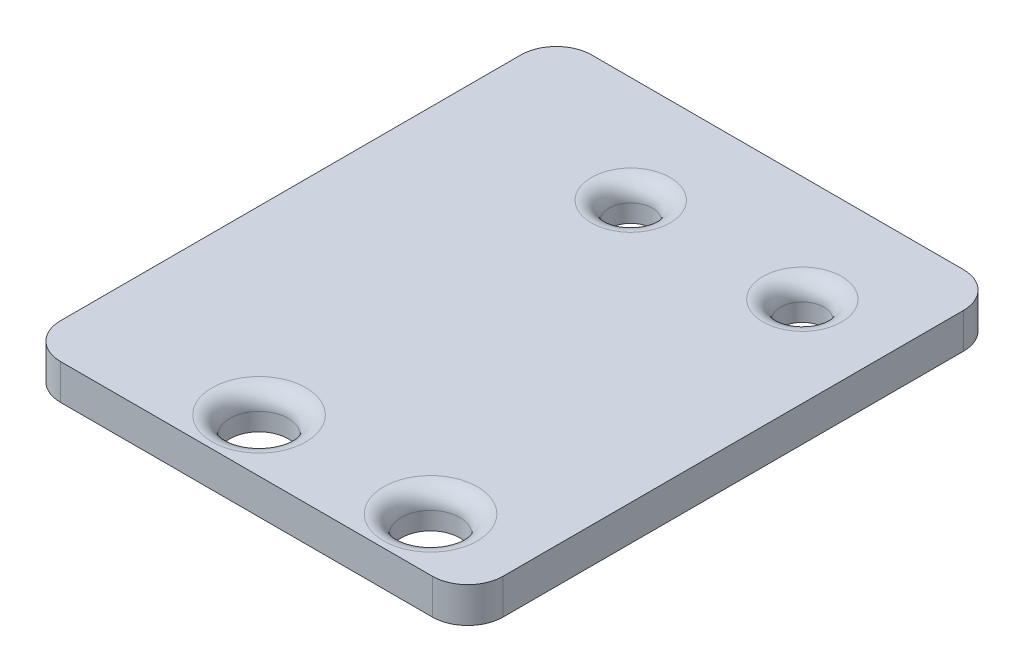
SolidWorks part; units mm, degrees
ref_plane "Front Plane" through (0, 0, 0) normal (0, 0, 1) x (1, 0, 0)
ref_plane "Top Plane" through (0, 0, 0) normal (0, 1, 0) x (1, 0, 0)
ref_plane "Right Plane" through (0, 0, 0) normal (1, 0, 0) x (0, 0, -1)
sketch "Sketch2" plane through (0, 0, 0) normal (0, 1, 0) x (1, 0, 0)
  line L0 (0, 0) -> (25, 0)
  line L1 (-13.75, 0) -> (13.75, 0) construction
  line L2 (25, 0) -> (25, 30)
  line L3 (25, 30) -> (0, 30)
  line L4 (0, -16.5) -> (0, 16.5) construction
  line L5 (0, 30) -> (0, 0)
  circle A0 centre (19.9, 24) radius 1.225
  circle A1 centre (10.21, 24) radius 1.225
  circle A2 centre (10.21, 3) radius 1.65
  circle A3 centre (19.9, 3) radius 1.65
  point P17 (0, 0)
  dimension "D3" = 5.1
  dimension "D4" = 6
  dimension "D5" = 2.45
  dimension "D6" = 6
  dimension "D7" = 9.69
  dimension "D8" = 2.45
  dimension "D10" = 10.21
  dimension "D12" = 3.3
  dimension "D13" = 3.3
  dimension "D14" = 3
  dimension "D1" = 25
  dimension "D2" = 30
  dimension "D9" = 24
  dimension "D11" = 3
  dimension "D15" = 5.1
extrude "Boss-Extrude2" add sketch "Sketch2" along normal blind 2
fillet "Fillet1" radius 2 4 edges at (0, 1, -30) (0, 1, 0) (25, 1, 0) (25, 1, -30)
fillet "Fillet2" radius 1 4 edges at (19.9, 2, -1.35) (10.21, 2, -1.35) (19.9, 2, -22.775) (10.21, 2, -22.775)
